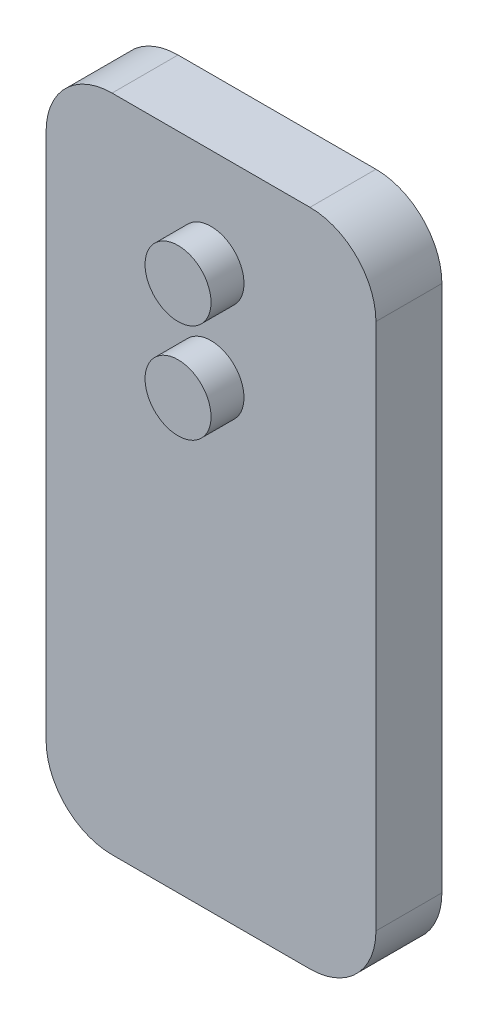
SolidWorks part; units mm, degrees
ref_plane "Plan de face" through (0, 0, 0) normal (0, 0, 1) x (1, 0, 0)
ref_plane "Plan de dessus" through (0, 0, 0) normal (0, 1, 0) x (1, 0, 0)
ref_plane "Plan de droite" through (0, 0, 0) normal (1, 0, 0) x (0, 0, -1)
sketch "Esquisse1" plane through (0, 0, 0) normal (0, 0, 1) x (1, 0, 0)
  line L0 (-15, 0) -> (15, 0)
  line L1 (25, 10) -> (25, 90)
  line L2 (15, 100) -> (-15, 100)
  line L3 (-25, 90) -> (-25, 10)
  arc A0 (-15, 0) -> (-25, 10) centre (-15, 10) cw
  arc A1 (15, 0) -> (25, 10) centre (15, 10) ccw
  arc A2 (15, 100) -> (25, 90) centre (15, 90) cw
  arc A3 (-25, 90) -> (-15, 100) centre (-15, 90) cw
  point P4 (0, 0)
  dimension "D1" = 10
  dimension "D2" = 50
  dimension "D3" = 100
extrude "Boss.-Extru.1" add sketch "Esquisse1" along normal blind 10
sketch "Esquisse2" plane through (0, 0, 10) normal (0, 0, 1) x (1, 0, 0)
  line L0 (0, 100) -> (0, 0) construction
  line L1 (15, 100) -> (-15, 100) construction
  line L2 (-15, 0) -> (15, 0) construction
  line L3 (-25, 50) -> (25, 50) construction
  line L4 (-25, 90) -> (-25, 10) construction
  line L5 (25, 10) -> (25, 90) construction
  circle A0 centre (0, 85) radius 5
  circle A1 centre (0, 70) radius 5
  dimension "D2" = 10
  dimension "D4" = 10
  dimension "D1" = 15
  dimension "D3" = 20
extrude "Boss.-Extru.2" add sketch "Esquisse2" along normal blind 5
